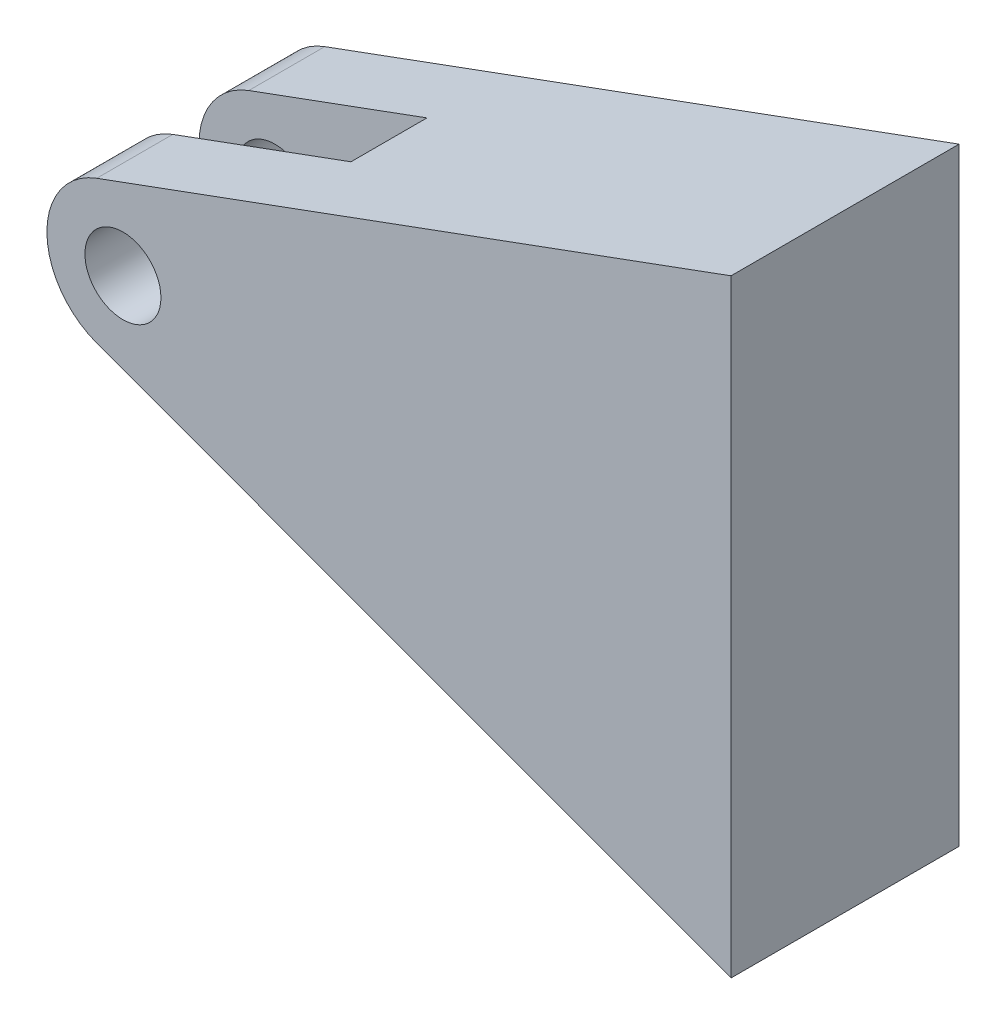
SolidWorks part; units mm, degrees
material "1023 Carbon Steel Sheet (SS)"
ref_plane "Front Plane" through (0, 0, 0) normal (0, 0, 1) x (1, 0, 0)
ref_plane "Top Plane" through (0, 0, 0) normal (0, 1, 0) x (1, 0, 0)
ref_plane "Right Plane" through (0, 0, 0) normal (1, 0, 0) x (0, 0, -1)
sketch "Sketch1" plane through (0, 0, 0) normal (0, 0, 1) x (1, 0, 0)
  line L0 (0, 0) -> (40, 0) construction
  line L1 (40, 20) -> (40, 0) construction
  line L2 (40, 20) -> (-1.722, 4.6941)
  line L3 (40, 20) -> (40, 0)
  line L4 (40, 0) -> (40, -20)
  line L5 (40, -20) -> (-1.722, -4.6941)
  circle A0 centre (0, 0) radius 2.5
  arc A1 (-1.722, 4.6941) -> (-1.722, -4.6941) centre (0, 0) ccw
  dimension "D1" = 5
  dimension "D2" = 5
  dimension "D3" = 40
  dimension "D4" = 20
extrude "Boss-Extrude1" add sketch "Sketch1" along normal blind 15
sketch "Sketch2" plane through (40, 0, 0) normal (1, 0, 0) x (0, 0, -1)
  line L0 (-15, 20) -> (0, -20) construction
  line L1 (0, 20) -> (-15, -20) construction
  line L2 (-15, 20) -> (0, 20) construction
  line L3 (-10, -20) -> (-5, -20)
  line L4 (-10, -20) -> (-10, 20)
  line L5 (-10, 20) -> (-5, 20)
  line L6 (-5, -20) -> (-5, 20)
  line L7 (-10, -20) -> (-5, 20) construction
  line L8 (-10, 20) -> (-5, -20) construction
  point P8 (-7.5, 0)
  dimension "D1" = 5
extrude "Cut-Extrude1" cut sketch "Sketch2" against normal through all from offset 30
